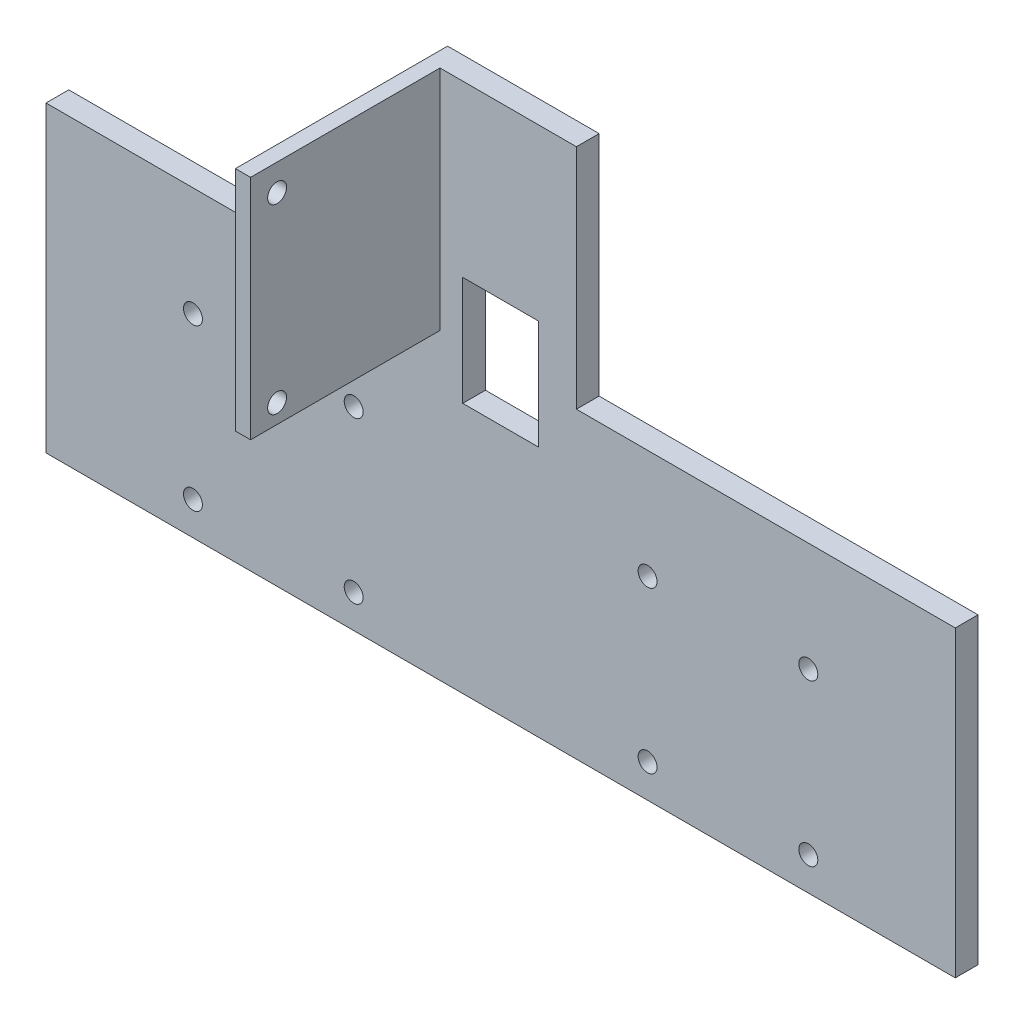
SolidWorks part; units mm, degrees
ref_plane "前视基准面" through (0, 0, 0) normal (0, 0, 1) x (1, 0, 0)
ref_plane "上视基准面" through (0, 0, 0) normal (0, 1, 0) x (1, 0, 0)
ref_plane "右视基准面" through (0, 0, 0) normal (1, 0, 0) x (0, 0, -1)
sketch "草图1" plane through (0, 0, 0) normal (0, 0, 1) x (1, 0, 0)
  line L0 (0, 30) -> (0, -20) construction
  line L2 (-60, 20) -> (-60, -20)
  line L3 (-60, -20) -> (60, -20)
  line L4 (60, 20) -> (60, -20)
  line L5 (-60, 20) -> (60, -20) construction
  line L6 (-60, -20) -> (60, 20) construction
  line L7 (-60, 20) -> (-10, 20)
  line L8 (60, 20) -> (10, 20)
  line L9 (-10, 20) -> (-10, 50)
  line L10 (-10, 50) -> (10, 50)
  line L11 (10, 50) -> (10, 20)
  point P0 (0, 0)
  dimension "D1" = 120
  dimension "D2" = 40
  dimension "D3" = 30
  dimension "D4" = 20
extrude "凸台-拉伸1" add sketch "草图1" along normal blind 3
sketch "草图2" plane through (0, 0, 3) normal (0, 0, 1) x (1, 0, 0)
  line L1 (-10, 50) -> (-8, 50)
  line L2 (-10, 50) -> (-10, 20)
  line L3 (-10, 20) -> (-8, 20)
  line L4 (-8, 50) -> (-8, 20)
  dimension "D1" = 2
extrude "凸台-拉伸2" add sketch "草图2" along normal blind 25
sketch "草图5" plane through (0, 0, 3) normal (0, 0, 1) x (1, 0, 0)
  line L6 (0, 35) -> (0, 20) construction
  line L7 (5, 27.5) -> (5, 27.5705) construction
  line L8 (-5, 27.5) -> (-5, 27.5705) construction
  line L9 (-5, 27.5705) -> (-5, 13.1681)
  line L10 (-5, 13.1681) -> (5, 13.1681)
  line L11 (5, 13.1681) -> (5, 27.5705)
  line L12 (5, 27.5705) -> (-5, 27.5705)
extrude "切除-拉伸1" cut sketch "草图5" against normal up to next
hole_wizard "M3 螺纹孔2" positions "草图13" profile "草图14" tap size "M3" standard "GB" end condition up to next
sketch "草图13" plane through (-10, 0, 0) normal (-1, 0, 0) x (0, 0, 1)
  point P0 (24.5, 46.5)
  point P3 (24.5, 22.5)
sketch "草图14" plane through (-10, 46.5, 24.5) normal (0, 1, 0) x (0, 0, 1)
  line L0 (0, 0) -> (0, 2)
  line L1 (0, 2) -> (1.25, 2)
  line L2 (1.25, 2) -> (1.25, 0)
  line L5 (1.25, 0) -> (0, 0)
  line L11 (0, -6.35) -> (0, 107.95) construction
  dimension "通孔螺纹孔钻头直径" = 2.5
  dimension "通孔螺纹孔钻头深度" = 2
cosmetic thread "孔螺蚊线3" parameters "D2"=3
cosmetic thread "孔螺蚊线4" parameters "D2"=3
hole_wizard "M3 螺纹孔3" positions "草图15" profile "草图16" tap size "M3" standard "GB" end condition up to next
sketch "草图15" plane through (0, 0, 3) normal (0, 0, 1) x (1, 0, 0)
  point P0 (-40.6066, 5.6066)
  point P3 (-19.3934, 5.6066)
  point P6 (-19.3934, -15.6066)
  point P9 (-40.6066, -15.6066)
  point P12 (19.3934, 5.6066)
  point P15 (40.6066, 5.6066)
  point P18 (19.3934, -15.6066)
  point P21 (40.6066, -15.6066)
sketch "草图16" plane through (-40.6066, 5.6066, 3) normal (1, 0, 0) x (0, -1, 0)
  line L0 (0, 0) -> (0, 3)
  line L1 (0, 3) -> (1.25, 3)
  line L2 (1.25, 3) -> (1.25, 0)
  line L5 (1.25, 0) -> (0, 0)
  line L11 (0, -6.35) -> (0, 107.95) construction
  dimension "通孔螺纹孔钻头直径" = 2.5
  dimension "通孔螺纹孔钻头深度" = 3
cosmetic thread "孔螺蚊线28"
cosmetic thread "孔螺蚊线29"
cosmetic thread "孔螺蚊线30"
cosmetic thread "孔螺蚊线31"
cosmetic thread "孔螺蚊线32"
cosmetic thread "孔螺蚊线33"
cosmetic thread "孔螺蚊线34"
cosmetic thread "孔螺蚊线35"
sketch "草图17" plane through (0, 0, 3) normal (0, 0, 1) x (1, 0, 0)
  line L1 (-28, 12.5) -> (28, 12.5)
  line L2 (-28, 12.5) -> (-28, -12.5)
  line L3 (-28, -12.5) -> (28, -12.5)
  line L4 (28, 12.5) -> (28, -12.5)
  line L5 (-28, 12.5) -> (28, -12.5) construction
  line L6 (-28, -12.5) -> (28, 12.5) construction
  point P0 (0, 0)
  dimension "D1" = 56
  dimension "D2" = 25
